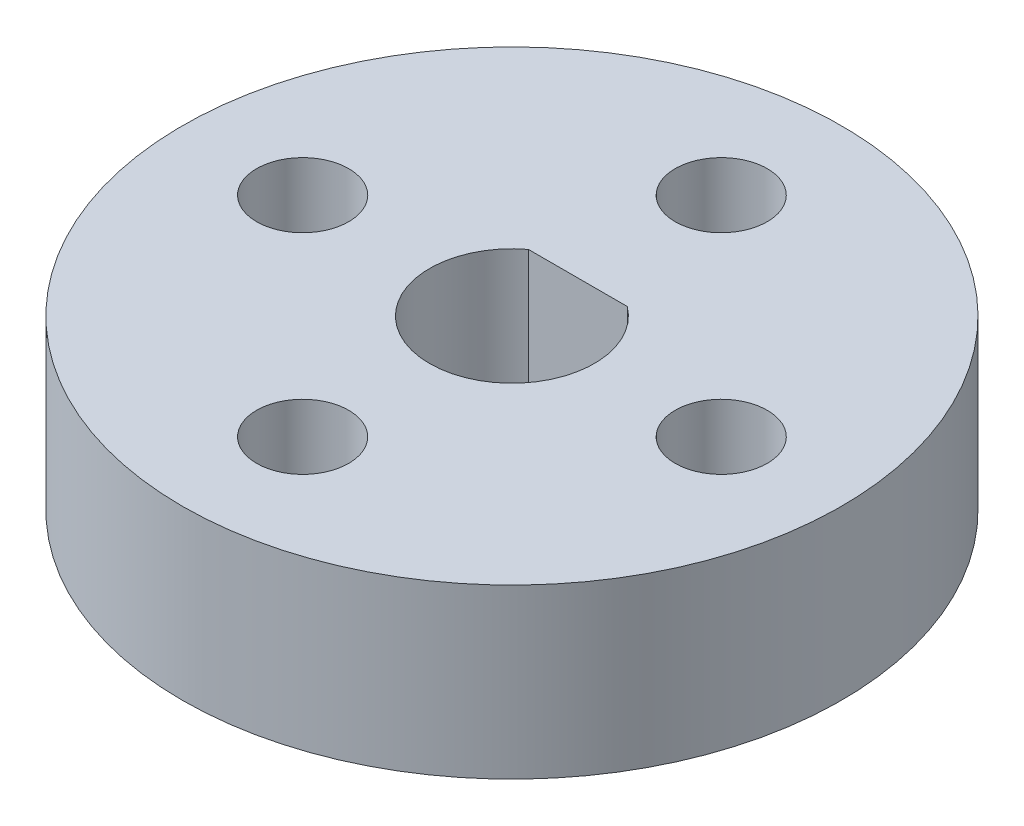
SolidWorks part; units mm, degrees
ref_plane "Front Plane" through (0, 0, 0) normal (0, 0, 1) x (1, 0, 0)
ref_plane "Top Plane" through (0, 0, 0) normal (0, 1, 0) x (1, 0, 0)
ref_plane "Right Plane" through (0, 0, 0) normal (1, 0, 0) x (0, 0, -1)
sketch "Sketch1" plane through (0, 0, 0) normal (0, 1, 0) x (1, 0, 0)
  line L0 (-1.5, 2) -> (1.5, 2)
  circle A0 centre (0, 0) radius 10
  circle A1 centre (0, 6.35) radius 1.397
  circle A2 centre (6.35, 0) radius 1.397
  circle A3 centre (0, -6.35) radius 1.397
  circle A4 centre (-6.35, 0) radius 1.397
  circle A5 centre (0, 0) radius 2.5
  point P14 (0, 0)
  dimension "D1" = 20
  dimension "D4" = 5
  dimension "D5" = 2.794
  dimension "D2" = 6.35
  dimension "D6" = 2
  dimension "D3" = 4
extrude "Boss-Extrude2" add sketch "Sketch1" along normal blind 5.1 contours L0 A5 | A0 A5 A4 A3 A2 A1
equation "\"scale\"= 1"
equation "\"i\"= 5"
equation "\"o\"= 2.794"
equation "\"d\"= \"i\" - 4.5"
equation "\"D5@Sketch1\"=\"o\""
equation "\"D4@Sketch1\"=\"i\""
